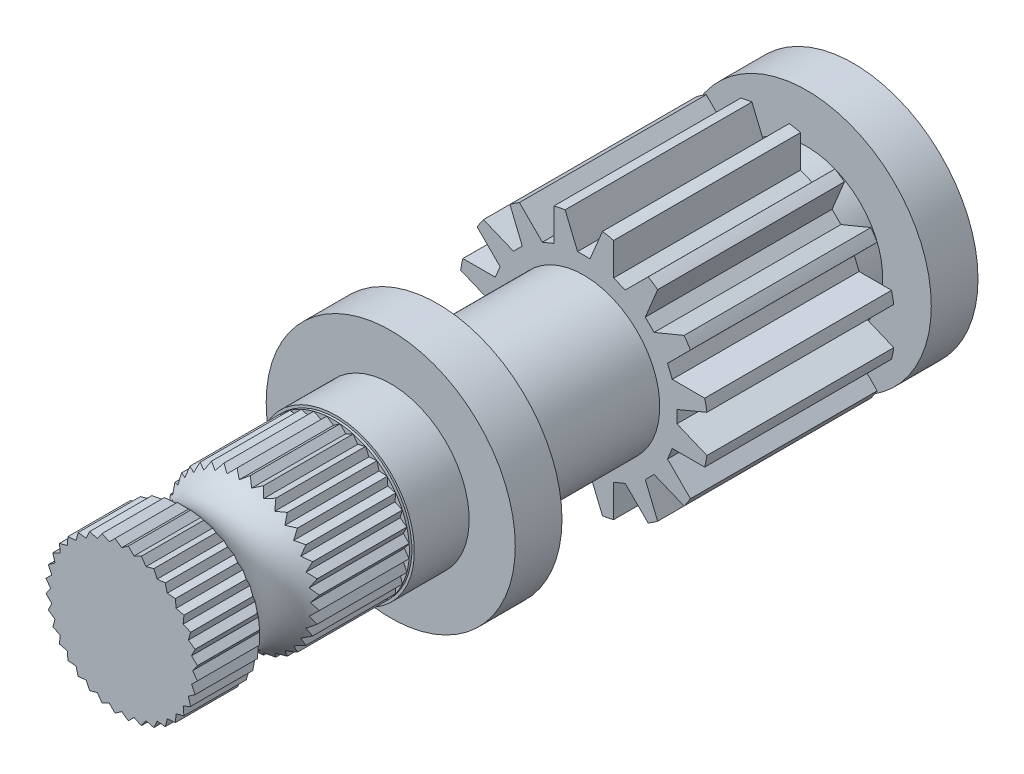
SolidWorks part; units mm, degrees
material "Plain Carbon Steel"
ref_plane "Front Plane" through (0, 0, 0) normal (0, 0, 1) x (1, 0, 0)
ref_plane "Top Plane" through (0, 0, 0) normal (0, 1, 0) x (1, 0, 0)
ref_plane "Right Plane" through (0, 0, 0) normal (1, 0, 0) x (0, 0, -1)
sketch "Sketch1" plane through (0, 0, 0) normal (0, 1, 0) x (1, 0, 0)
  line L0 (0, 0) -> (0, -95.2691) construction
  line L1 (0, 17.9705) -> (12.7, 17.9705)
  line L2 (12.7, 17.9705) -> (12.7, 13.208)
  line L3 (12.7, 13.208) -> (7.747, 13.208)
  line L4 (7.747, 13.208) -> (7.747, 9.525)
  line L5 (7.747, 9.525) -> (12.7, 9.525)
  line L6 (12.7, 9.525) -> (12.7, -9.525)
  line L7 (12.7, -9.525) -> (7.747, -9.525)
  line L8 (7.747, -9.525) -> (7.747, -24.4475)
  line L9 (7.747, -24.4475) -> (12.7, -24.4475)
  line L10 (12.7, -24.4475) -> (12.7, -29.21)
  line L11 (12.7, -29.21) -> (8.001, -29.21)
  line L12 (7.747, -34.798) -> (7.747, -44.196)
  line L13 (7.747, -50.292) -> (7.747, -56.642)
  line L14 (7.747, -56.642) -> (0, -56.642)
  line L15 (0, -56.642) -> (0, 17.9705)
  line L16 (0, 0) -> (8.001, 0) construction
  line L17 (7.747, -34.798) -> (8.001, -34.798)
  line L18 (8.001, -34.798) -> (8.001, -29.21)
  arc A0 (7.747, -44.196) -> (7.747, -50.292) centre (10.033, -47.244) ccw
  point P5 (6.223, -47.244)
  dimension "D1" = 25.4
  dimension "D2" = 25.4
  dimension "D3" = 15.494
  dimension "D4" = 12.446
  dimension "D5" = 6.096
  dimension "D6" = 27.432
  dimension "D7" = 74.6125
  dimension "D8" = 29.21
  dimension "D9" = 4.7625
  dimension "D10" = 4.7625
  dimension "D11" = 19.05
  dimension "D12" = 6.35
  dimension "D13" = 16.002
  dimension "D14" = 5.588
revolve "Revolve1" add sketch "Sketch1" angle 360 about L0
sketch "Sketch2" plane through (0, 0, 56.642) normal (0, 0, 1) x (1, 0, 0)
  line L0 (0, 0) -> (0, 14.806) construction
  line L1 (0, 0) -> (-1.2636, 14.4429) construction
  line L2 (0, 0) -> (1.2636, 14.4429) construction
  line L3 (-0.6752, 7.7175) -> (0, 7.239)
  line L4 (0, 7.239) -> (0.6752, 7.7175)
  circle A0 centre (0, 0) radius 7.239 construction
  circle A1 centre (0, 0) radius 7.747 construction
  arc A2 (0.6752, 7.7175) -> (-0.6752, 7.7175) centre (0, 0) ccw
  dimension "D2" = 14.478
  dimension "D1" = 10
extrude "Cut-Extrude1" cut sketch "Sketch2" against normal blind 21.59
pattern_circular "CirPattern1" count 36 over 360 about axis through (0, 0, 0) along (0, 0, 1) of "Cut-Extrude1"
sketch "Sketch3" plane through (0, 0, 0) normal (0, 0, 1) x (1, 0, 0)
  line L0 (0, 0) -> (0, 15.7598) construction
  line L1 (3.1985, 16.0797) -> (0, 0) construction
  line L2 (0, 0) -> (-3.1728, 15.9505) construction
  line L3 (-1.905, 12.5563) -> (-0.635, 9.5038)
  line L4 (1.905, 12.5563) -> (0.635, 9.5038)
  line L5 (-0.635, 9.5038) -> (0.635, 9.5038)
  circle A0 centre (0, 0) radius 12.7 construction
  arc A1 (1.905, 12.5563) -> (-1.905, 12.5563) centre (0, 0) ccw
  circle A2 centre (0, 0) radius 9.525 construction
  dimension "D1" = 19.05
  dimension "D2" = 22.5
  dimension "D3" = 3.81
  dimension "D4" = 0.5812
  dimension "D5" = 1.27
extrude "Cut-Extrude2" cut sketch "Sketch3" against normal up to next and the other way up to next
pattern_circular "CirPattern2" count 16 over 360 about axis through (0, 0, 0) along (0, 0, 1) of "Cut-Extrude2"
